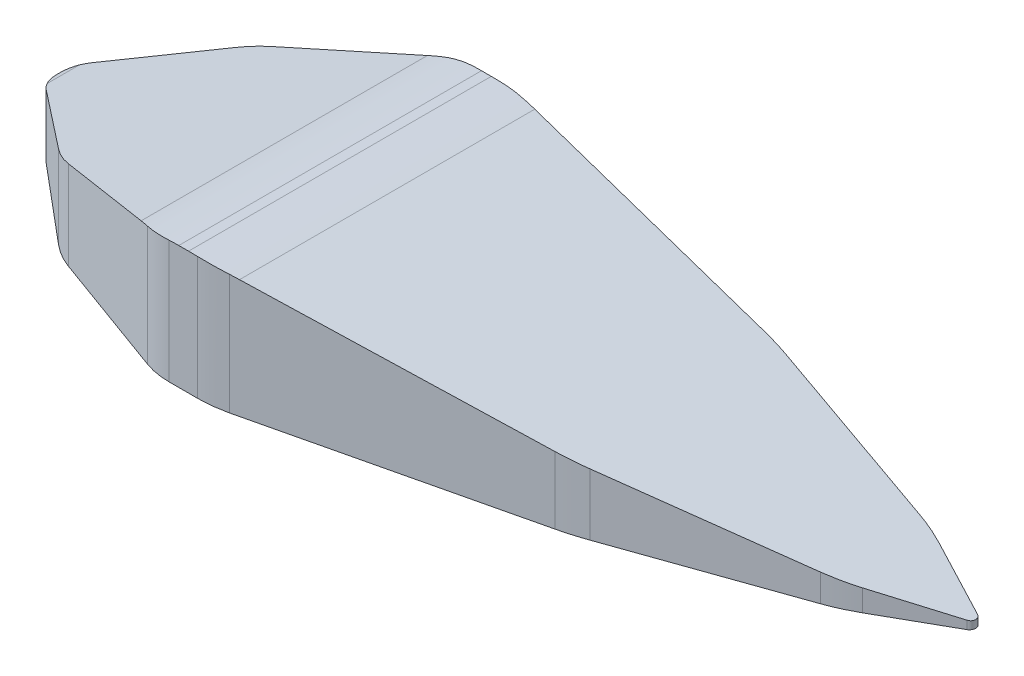
SolidWorks part; units mm, degrees
ref_plane "Front Plane" through (0, 0, 0) normal (0, 0, 1) x (1, 0, 0)
ref_plane "Top Plane" through (0, 0, 0) normal (0, 1, 0) x (1, 0, 0)
ref_plane "Right Plane" through (0, 0, 0) normal (1, 0, 0) x (0, 0, -1)
sketch "Sketch1" plane through (0, 0, 0) normal (0, 1, 0) x (1, 0, 0)
  line L0 (146.0698, 122.5671) -> (556.1483, 466.6637)
  line L1 (676.4552, 536.1229) -> (1335.1737, 775.877)
  line L2 (1471.9818, 800) -> (1622.7493, 800)
  line L3 (1779.1837, 787.6883) -> (3265.3831, 552.2976)
  line L4 (3418.9601, 519.6538) -> (4378.1346, 262.6437)
  line L5 (4541.9335, 203.0258) -> (4919.0165, 27.1892)
  line L6 (4919.0165, -27.1892) -> (4541.9335, -203.0258)
  line L7 (4378.1346, -262.6437) -> (3418.9601, -519.6538)
  line L8 (3265.3831, -552.2976) -> (1779.1837, -787.6883)
  line L9 (1622.7493, -800) -> (1471.9818, -800)
  line L10 (1335.1737, -775.877) -> (676.4552, -536.1229)
  line L11 (556.1483, -466.6637) -> (146.0698, -122.5671)
  arc A0 (146.0698, 122.5671) -> (146.0698, -122.5671) centre (248.9159, 0) ccw
  arc A1 (676.4552, -536.1229) -> (556.1483, -466.6637) centre (813.2633, -160.2459) cw
  arc A2 (1471.9818, -800) -> (1335.1737, -775.877) centre (1471.9818, -400) cw
  arc A3 (1335.1737, 775.877) -> (1471.9818, 800) centre (1471.9818, 400) cw
  arc A4 (556.1483, 466.6637) -> (676.4552, 536.1229) centre (813.2633, 160.2459) cw
  arc A5 (1779.1837, -787.6883) -> (1622.7493, -800) centre (1622.7493, 200) cw
  arc A6 (4541.9335, -203.0258) -> (4378.1346, -262.6437) centre (4119.3155, 703.2821) cw
  arc A7 (4378.1346, 262.6437) -> (4541.9335, 203.0258) centre (4119.3155, -703.2821) cw
  arc A8 (1622.7493, 800) -> (1779.1837, 787.6883) centre (1622.7493, -200) cw
  arc A9 (3418.9601, -519.6538) -> (3265.3831, -552.2976) centre (3030.7315, 929.2349) cw
  arc A10 (3265.3831, 552.2976) -> (3418.9601, 519.6538) centre (3030.7315, -929.2349) cw
  arc A11 (4919.0165, 27.1892) -> (4919.0165, -27.1892) centre (4906.3379, 0) cw
  point P15 (0, 0)
  point P18 (610.178, -512)
  point P21 (1401.451, -800)
  point P24 (1401.451, 800)
  point P27 (610.178, 512)
  point P30 (1701.451, -800)
  point P33 (4462.642, -240)
  point P36 (4462.642, 240)
  point P39 (1701.451, 800)
  point P42 (3343.027, -540)
  point P45 (3343.027, 540)
  point P48 (4977.324, 0)
  dimension "r0" = 160
  dimension "r1" = 400
  dimension "r3" = 1000
  dimension "r4" = 1500
  dimension "r6" = 30
  dimension "x1" = 610.178
  dimension "x2" = 1401.451
  dimension "x3" = 1701.451
  dimension "x4" = 3343.027
  dimension "x5" = 4462.642
  dimension "x6" = 4977.324
  dimension "x7" = 4462.642
  dimension "x8" = 3343.027
  dimension "x9" = 1701.451
  dimension "x10" = 1401.451
  dimension "x11" = 610.178
  dimension "y1" = 512
  dimension "y2" = 800
  dimension "y4" = 540
  dimension "y5" = 240
  dimension "y7" = 240
  dimension "y8" = 540
  dimension "y9" = 800
  dimension "y11" = 512
extrude "TopView_Extrude" add sketch "Sketch1" along normal blind 800
sketch "Sketch2" plane through (0, 0, 0) normal (0, 0, 1) x (1, 0, 0)
  line L0 (0, 300) -> (0, 332.8541)
  line L1 (113.6551, 478.3844) -> (1282.1337, 770.2016)
  line L2 (1524.433, 800) -> (1576.231, 800)
  line L3 (1825.6931, 784.3812) -> (4977.324, 388.181)
  line L4 (4977.324, 388.181) -> (4977.324, 355.91)
  line L5 (4977.324, 355.91) -> (1795.4573, 155.9089)
  line L6 (1607.2592, 150) -> (150, 150)
  arc A0 (0, 332.8541) -> (113.6551, 478.3844) centre (150, 332.8541) cw
  arc A1 (0, 300) -> (150, 150) centre (150, 300) ccw
  arc A2 (1282.1337, 770.2016) -> (1524.433, 800) centre (1524.433, -200) cw
  arc A3 (1576.231, 800) -> (1825.6931, 784.3812) centre (1576.231, -1200) cw
  arc A4 (1795.4573, 155.9089) -> (1607.2592, 150) centre (1607.2592, 3150) cw
  point P10 (0, 450)
  point P13 (0, 150)
  point P16 (1401.451, 800)
  point P19 (1701.451, 800)
  point P22 (1701.451, 150)
  dimension "r0" = 150
  dimension "r2" = 1000
  dimension "r3" = 2000
  dimension "r6" = 3000
  dimension "x2" = 1401.451
  dimension "x3" = 1701.451
  dimension "x4" = 4977.324
  dimension "x6" = 1701.451
  dimension "y0" = 150
  dimension "y1" = 450
  dimension "y2" = 800
  dimension "y4" = 388.181
  dimension "y5" = 355.91
extrude "SideProfile_Cut" cut sketch "Sketch2" against normal through all and the other way through all flip side to cut
